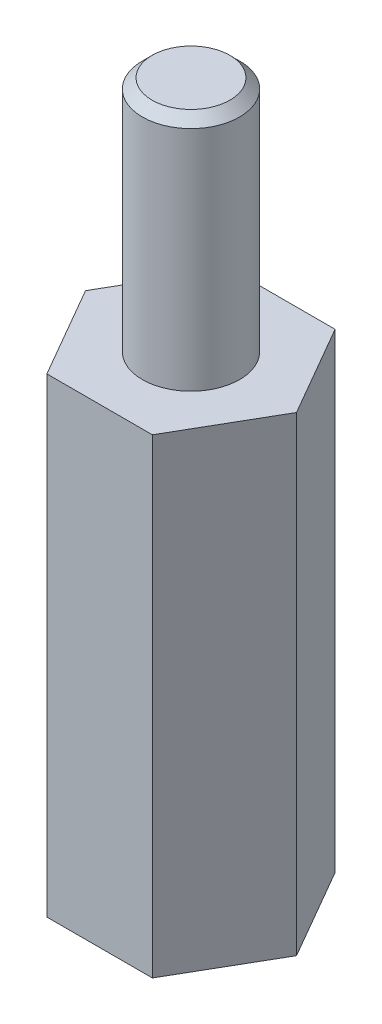
SolidWorks part; units mm, degrees
material "Nylon 101"
ref_plane "Front Plane" through (0, 0, 0) normal (0, 0, 1) x (1, 0, 0)
ref_plane "Top Plane" through (0, 0, 0) normal (0, 1, 0) x (1, 0, 0)
ref_plane "Right Plane" through (0, 0, 0) normal (1, 0, 0) x (0, 0, -1)
sketch "Sketch1" plane through (0, 0, 0) normal (0, 1, 0) x (1, 0, 0)
  line L1 (2.7135, 0) -> (1.3568, 2.35)
  line L2 (1.3568, 2.35) -> (-1.3568, 2.35)
  line L3 (-1.3568, 2.35) -> (-2.7135, 0)
  line L4 (-2.7135, 0) -> (-1.3568, -2.35)
  line L5 (-1.3568, -2.35) -> (1.3568, -2.35)
  line L6 (1.3568, -2.35) -> (2.7135, 0)
  circle A0 centre (0, 0) radius 2.35 construction
  point P1 (0, 0)
  dimension "D1" = 4.7
extrude "Boss-Extrude1" add sketch "Sketch1" along normal blind 12.1
sketch "Sketch2" plane through (0, 12.1, 0) normal (0, 1, 0) x (1, 0, 0)
  circle A0 centre (0, 0) radius 1.25
  dimension "D1" = 2.5
extrude "Boss-Extrude2" add sketch "Sketch2" along normal blind 6.1
chamfer "Chamfer1" distance 0.25 angle 45 1 edges at (0, 18.2, 1.25)
sketch "Sketch3" plane through (0, 0, 0) normal (0, -1, 0) x (1, 0, 0)
  circle A0 centre (0, 0) radius 1.25
  dimension "D1" = 2.5
extrude "Cut-Extrude1" cut sketch "Sketch3" against normal blind 10
